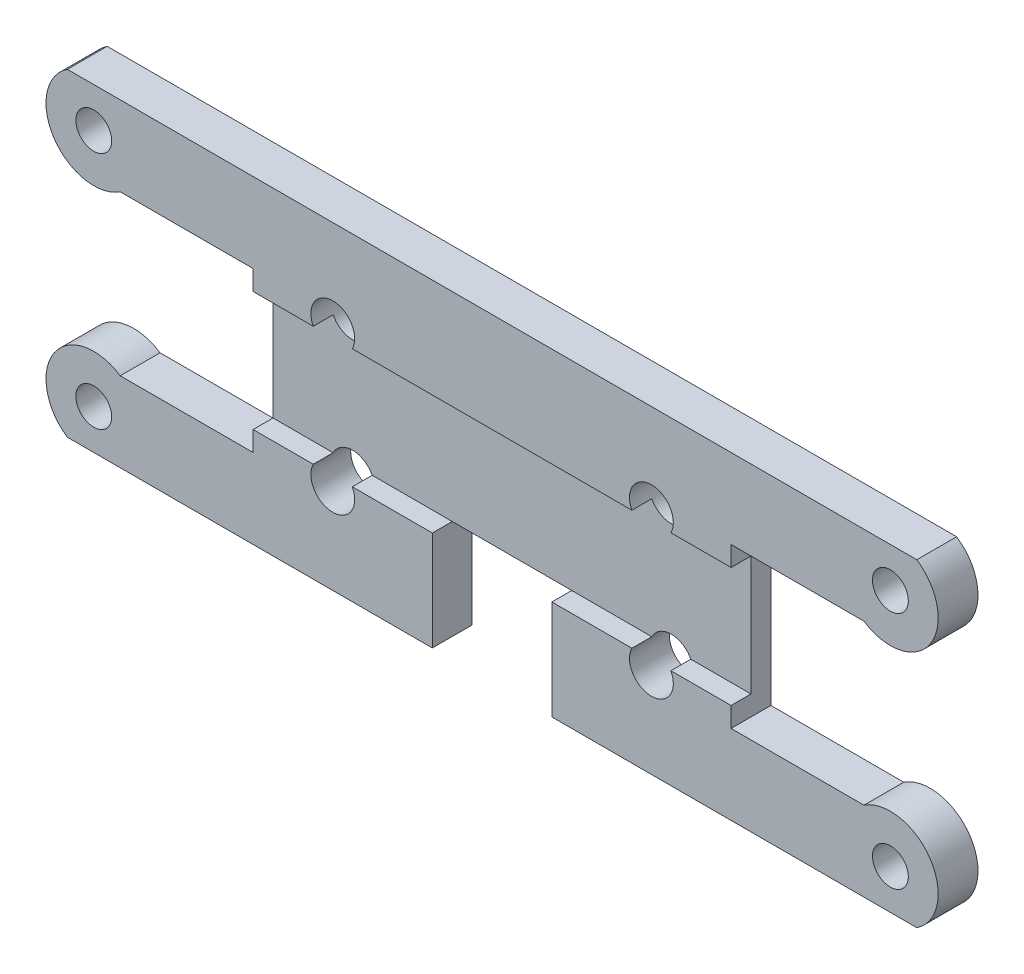
SolidWorks part; units mm, degrees
ref_plane "Alzado" through (0, 0, 0) normal (0, 0, 1) x (1, 0, 0)
ref_plane "Planta" through (0, 0, 0) normal (0, 1, 0) x (1, 0, 0)
ref_plane "Vista lateral" through (0, 0, 0) normal (1, 0, 0) x (0, 0, -1)
sketch "Croquis1" plane through (0, 0, 0) normal (0, 0, 1) x (1, 0, 0)
  line L0 (0, 0) -> (7143.243, 0) construction
  line L1 (0, 0) -> (0, 7143.243) construction
  line L3 (-1.3266, 8) -> (20, 8)
  line L4 (20, 8) -> (20, 0)
  line L5 (20, 0) -> (8, 0)
  line L6 (8, 0) -> (8, 4)
  line L7 (8, 4) -> (1.3266, 4)
  line L8 (10.8753, 7) -> (-12.9398, 7) construction
  line L9 (5.6569, 7) -> (8, 4) construction
  circle A0 centre (0, 6) radius 0.9
  arc A1 (-1.3266, 8) -> (1.3266, 4) centre (0, 6) ccw
  circle A2 centre (12, 3.5) radius 1.1
  circle A3 centre (0, 0) radius 9 construction
  dimension "D1" = 6
  dimension "1,8" = 1.8
  dimension "D2" = 2.4
  dimension "D5" = 7
  dimension "2,2" = 2.2
  dimension "D7" = 18
  dimension "D3" = 8
  dimension "D4" = 8
  dimension "D6" = 12
  dimension "8" = 8
  dimension "D8" = 7
  dimension "D9" = 20
extrude "Saliente-Extruir1" add sketch "Croquis1" along normal blind 2
sketch "Croquis2" plane through (0, 0, 2) normal (0, 0, 1) x (1, 0, 0)
  line L0 (20, 0) -> (20, 8) construction
  line L1 (8, 0) -> (20, 0)
  line L2 (8, 0) -> (8, 3)
  line L3 (8, 3) -> (20, 3)
  line L4 (20, 0) -> (20, 3)
  dimension "D1" = 3
extrude "Cortar-Extruir1" cut sketch "Croquis2" against normal blind 1
mirror "Simetría1" about plane through (20, 0, 2) normal (0, 1, 0) of bodies 103 101
mirror "Simetría2" about plane through (20, 8, 2) normal (-1, 0, 0) of bodies 102
sketch "Croquis3" plane through (0, 0, 2) normal (0, 0, 1) x (1, 0, 0)
  line L0 (41.3266, -8) -> (-1.3266, -8) construction
  line L1 (17, -13) -> (23, -13)
  line L2 (17, -13) -> (17, -3)
  line L3 (17, -3) -> (23, -3)
  line L4 (23, -13) -> (23, -3)
  line L5 (17, -13) -> (23, -3) construction
  line L6 (17, -3) -> (23, -13) construction
  line L7 (27.0202, -3) -> (12.9798, -3) construction
  point P0 (20, -8)
  dimension "D1" = 6
extrude "Cortar-Extruir2" cut sketch "Croquis3" against normal through all
